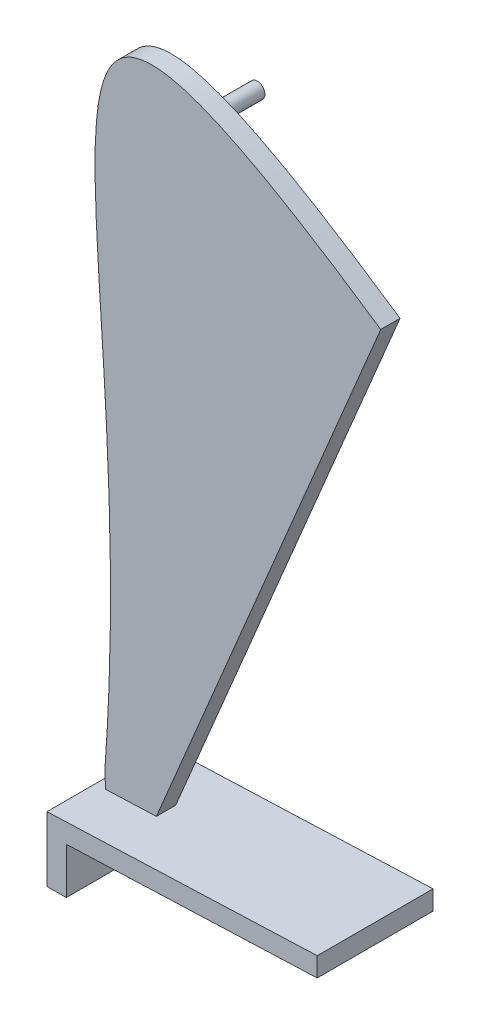
SolidWorks part; units mm, degrees
material "Hexcel AS4C (3000 Filaments)"
ref_plane "Front Plane" through (0, 0, 0) normal (0, 0, 1) x (1, 0, 0)
ref_plane "Top Plane" through (0, 0, 0) normal (0, 1, 0) x (1, 0, 0)
ref_plane "Right Plane" through (0, 0, 0) normal (1, 0, 0) x (0, 0, -1)
sketch "Sketch1" plane through (0, 0, 0) normal (0, 0, 1) x (1, 0, 0)
  line L0 (-65, 0) -> (65, 0) construction
  line L1 (-65, 0) -> (-65, 10) construction
  line L2 (65, 0) -> (65, 15) construction
  line L3 (-65, 10) -> (65, 15) construction
  line L4 (-66, 10.9623) -> (-1, 13.4623)
  line L5 (-66, -1) -> (-66, 10.9623)
  line L8 (-71, -1) -> (-71, 15.7737)
  line L9 (-71, 15.7737) -> (-1, 18.466)
  line L11 (-1, 13.4623) -> (-1, 18.466)
  line L12 (-71, -6) -> (65, -6) construction
  line L13 (-66, -1) -> (65, -1) construction
  line L14 (-71, 15.7737) -> (64.7694, 20.9956) construction
  line L15 (-66, 10.9623) -> (64.9616, 15.9993) construction
  line L16 (-66, -1) -> (-71, -1)
  line L17 (-71, -6) -> (-71, 15.7737) construction
  point P3 (0, 0)
  dimension "D1" = 130
  dimension "D2" = 15
  dimension "D3" = 10
  dimension "D6" = 70
  dimension "D4" = 1
  dimension "D5" = 5
extrude "Boss-Extrude1" add sketch "Sketch1" along normal mid plane 30
sketch "Sketch2" plane through (0, 0, 0) normal (0, 0, 1) x (1, 0, 0)
  line L0 (-68.3293, 15.8764) -> (-68.4961, 20.2121)
  line L1 (-1, 18.466) -> (-71, 15.7737) construction
  line L2 (-55.1599, 16.3829) -> (2.9611, 154.665)
  line L3 (-55.1599, 16.3829) -> (-68.3293, 15.8764)
  line L4 (-94.8812, 50.9186) -> (-0.1318, 276.3471) construction
  spline S0 degree 3 poles (-68.4961, 20.2121) (-58.4462, 154.1875) (-107.8565, 229.8205) (2.9611, 154.665) knots 0 0 0 0 1 1 1 1
  dimension "D3" = 50
  dimension "D1" = 65
  dimension "D2" = 150
extrude "Boss-Extrude2" add sketch "Sketch2" along normal mid plane 5
sketch "Sketch3" plane through (0, 0, -2.5) normal (0, 0, -1) x (-1, 0, 0)
  line L0 (49.0389, 183.3012) -> (49.0389, 145.4194) construction
  line L1 (24.9988, 172.3829) -> (69.4672, 172.3829) construction
  circle A1 centre (49.0389, 172.3829) radius 2
  spline S0 degree 3 poles (-2.9611, 154.665) (107.8565, 229.8205) (58.4462, 154.1875) (68.4961, 20.2121) knots 0 0 0 0 1 1 1 1 construction
  dimension "D1" = 4
  dimension "D2" = 52
  dimension "D3" = 156
extrude "Boss-Extrude3" add sketch "Sketch3" along normal blind 15
